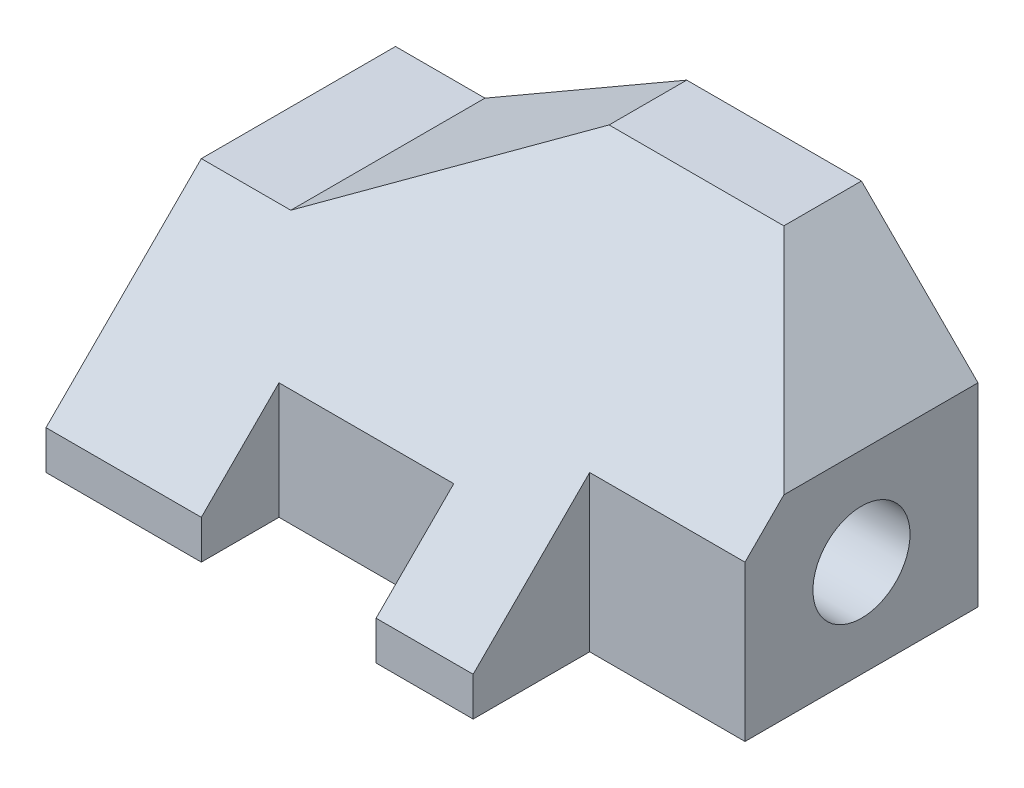
SolidWorks part; units mm, degrees
material "AISI 1020"
ref_plane "Plane1" through (0, 0, 0) normal (0, 0, 1) x (1, 0, 0)
ref_plane "Plane2" through (0, 0, 0) normal (0, 1, 0) x (1, 0, 0)
ref_plane "Plane3" through (0, 0, 0) normal (1, 0, 0) x (0, 0, -1)
sketch "Esquisse1" plane through (0, 0, 0) normal (0, 1, 0) x (1, 0, 0)
  line L1 (0, 0) -> (95.25, 0)
  line L2 (0, 0) -> (0, 57.15)
  line L3 (0, 57.15) -> (95.25, 57.15)
  line L4 (95.25, 0) -> (95.25, 57.15)
  dimension "D1" = 57.15
  dimension "D2" = 95.25
extrude "Base-Extrusion" add sketch "Esquisse1" along normal blind 50.8
sketch "Esquisse2" plane through (95.25, 0, 0) normal (1, 0, 0) x (0, 0, -1)
  line L0 (44.45, 50.8) -> (0, 6.35)
  line L1 (0, 50.8) -> (57.15, 50.8) construction
  line L2 (0, 50.8) -> (0, 0) construction
  line L3 (0, 6.35) -> (0, 50.8)
  line L4 (0, 50.8) -> (44.45, 50.8)
  line L5 (57.15, 50.8) -> (57.15, 0) construction
  dimension "D1" = 12.7
  dimension "D2" = 45
extrude "Enlèv. mat.-Extru.1" cut sketch "Esquisse2" against normal through all
sketch "Esquisse3" plane through (0, 0, 0) normal (0, -1, 0) x (1, 0, 0)
  line L0 (0, 0) -> (95.25, 0) construction
  line L1 (69.85, 0) -> (95.25, 0)
  line L2 (69.85, 0) -> (69.85, -19.05)
  line L3 (69.85, -19.05) -> (95.25, -19.05)
  line L4 (95.25, 0) -> (95.25, -19.05)
  line L5 (95.25, 0) -> (95.25, -57.15) construction
  line L6 (0, -57.15) -> (0, 0) construction
  line L7 (25.4, 0) -> (53.975, 0)
  line L8 (25.4, 0) -> (25.4, -12.7)
  line L9 (25.4, -12.7) -> (53.975, -12.7)
  line L10 (53.975, 0) -> (53.975, -12.7)
  dimension "D1" = 25.4
  dimension "D2" = 19.05
  dimension "D3" = 25.4
  dimension "D4" = 28.575
  dimension "D5" = 12.7
extrude "Enlèv. mat.-Extru.2" cut sketch "Esquisse3" against normal through all
chamfer "Chanfrein1" distance 19.05 angle 45 1 edges at (95.25, 50.8, -50.8)
sketch "Esquisse4" plane through (0, 0, -57.15) normal (0, 0, -1) x (-1, 0, 0)
  line L0 (0, 50.8) -> (-47.625, 50.8)
  line L1 (-76.2, 50.8) -> (0, 50.8) construction
  line L2 (-47.625, 50.8) -> (-14.6294, 31.75)
  line L3 (-14.6294, 31.75) -> (0, 31.75)
  line L4 (0, 50.8) -> (0, 0) construction
  line L5 (0, 31.75) -> (0, 50.8)
  dimension "D1" = 30
  dimension "D2" = 28.575
  dimension "D3" = 19.05
extrude "Enlèv. mat.-Extru.3" cut sketch "Esquisse4" against normal through all
hole_wizard "Diamètre du perçage 5/8 (0.625)2" positions "Esquisse6" profile "Esquisse5" hole size "5/8" standard "Ansi Inch"
sketch "Esquisse6" plane through (95.25, 0, 0) normal (1, 0, 0) x (0, 0, -1)
  line L0 (57.15, 31.75) -> (57.15, 0) construction
  line L1 (19.05, 0) -> (57.15, 0) construction
  point P0 (38.1, 15.875)
  dimension "D1" = 19.05
  dimension "D2" = 15.875
sketch "Esquisse5" plane through (95.25, 15.875, -38.1) normal (0, 1, 0) x (0, 0, -1)
  line L0 (0, 0) -> (0, 36.5193)
  line L1 (0, 36.5193) -> (7.9375, 31.75)
  line L2 (7.9375, 31.75) -> (7.9375, 0)
  line L5 (7.9375, 0) -> (0, 0)
  line L10 (0, 36.5193) -> (-7.9375, 31.75) construction
  line L11 (0, -6.35) -> (0, 107.95) construction
  dimension "Diamètre du perçage" = 15.875
  dimension "Profondeur du perçage" = 31.75
  dimension "Angle de pointe" = 118
